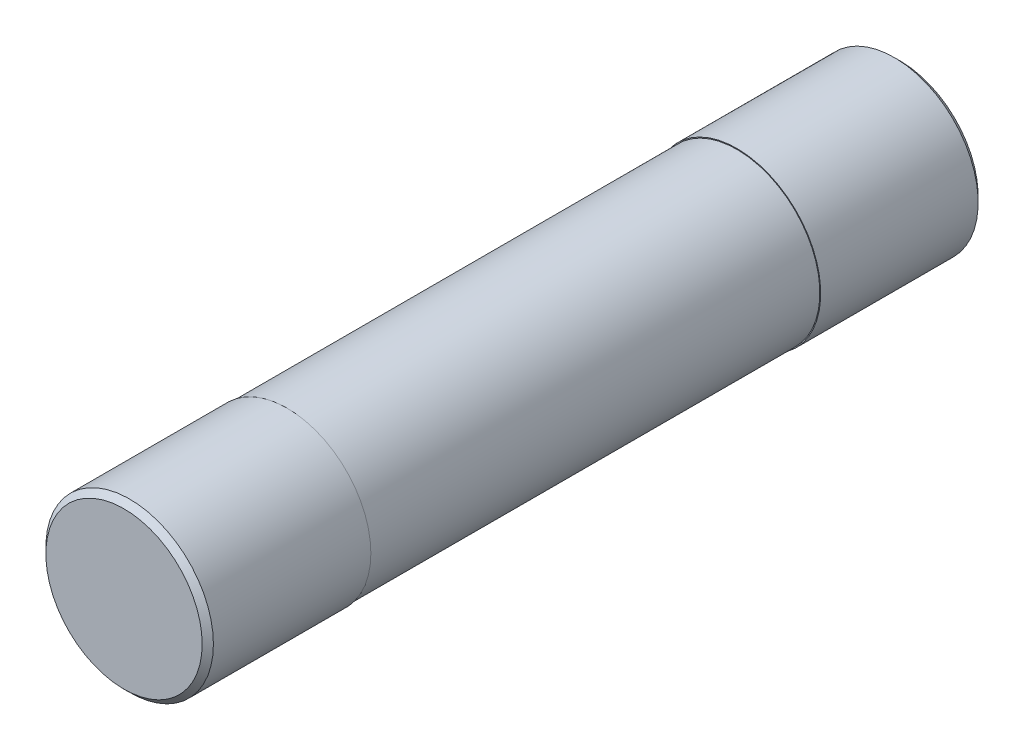
SolidWorks part; units mm, degrees
ref_plane "정면" through (0, 0, 0) normal (0, 0, 1) x (1, 0, 0)
ref_plane "윗면" through (0, 0, 0) normal (0, 1, 0) x (1, 0, 0)
ref_plane "우측면" through (0, 0, 0) normal (1, 0, 0) x (0, 0, -1)
sketch "스케치1" plane through (0, 0, 0) normal (0, 0, 1) x (1, 0, 0)
  circle A0 centre (0, 0) radius 1.475
  dimension "D1" = 2.95
extrude "보스-돌출1" add sketch "스케치1" along normal blind 8
sketch "스케치2" plane through (0, 0, 0) normal (0, 0, -1) x (-1, 0, 0)
  circle A0 centre (0, 0) radius 1.49
  dimension "D1" = 2.98
extrude "보스-돌출2" add sketch "스케치2" along normal blind 2.9
sketch "스케치3" plane through (0, 0, 8) normal (0, 0, 1) x (1, 0, 0)
  circle A0 centre (0, 0) radius 1.49
  dimension "D1" = 2.98
extrude "보스-돌출3" add sketch "스케치3" along normal blind 2.9
chamfer "모따기1" distance 0.1 angle 45 2 edges at (1.49, 0, 10.9) (-1.49, 0, -2.9)
